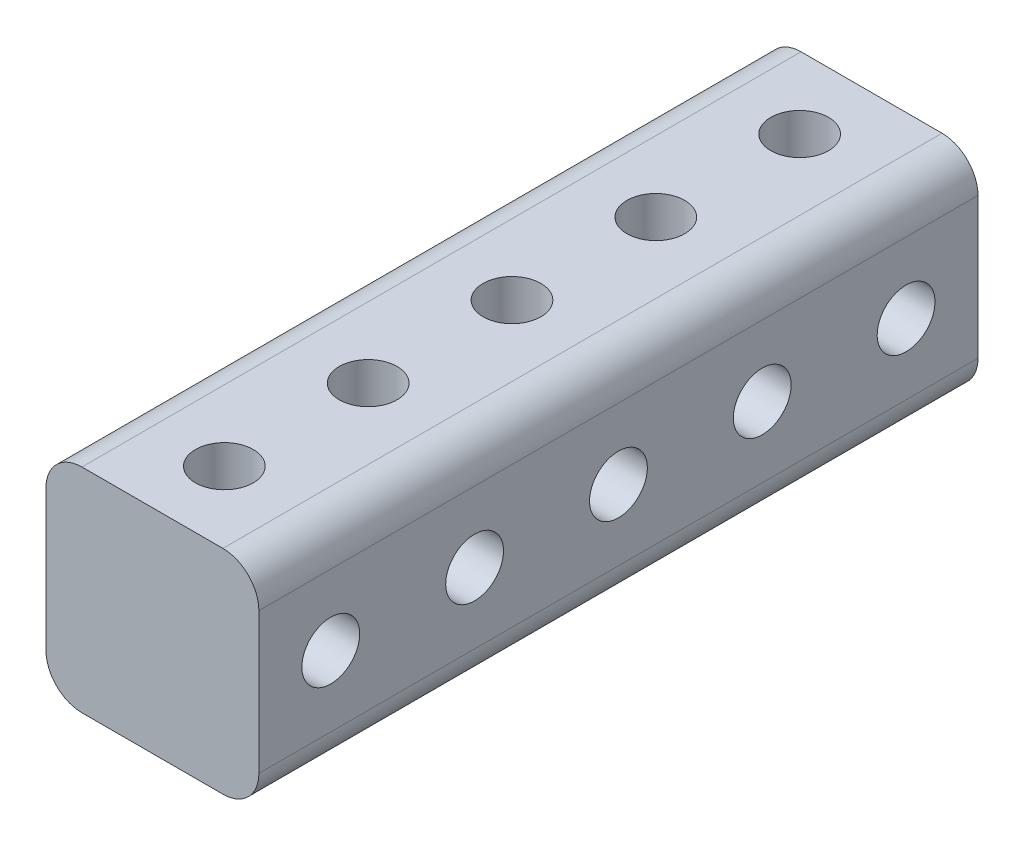
SolidWorks part; units mm, degrees
material "PET"
ref_plane "Front Plane" through (0, 0, 0) normal (0, 0, 1) x (1, 0, 0)
ref_plane "Top Plane" through (0, 0, 0) normal (0, 1, 0) x (1, 0, 0)
ref_plane "Right Plane" through (0, 0, 0) normal (1, 0, 0) x (0, 0, -1)
sketch "Sketch1" plane through (0, 0, 0) normal (0, 0, 1) x (1, 0, 0)
  line L1 (0, 0) -> (18.796, 0)
  line L2 (0, 0) -> (0, 18.796)
  line L3 (0, 18.796) -> (18.796, 18.796)
  line L4 (18.796, 0) -> (18.796, 18.796)
  dimension "D1" = 18.796
extrude "Boss-Extrude1" add sketch "Sketch1" along normal blind 63.5
fillet "Fillet1" radius 3.175 4 edges at (0, 18.796, 31.75) (18.796, 0, 31.75) (0, 0, 31.75) (18.796, 18.796, 31.75)
sketch "Sketch2" plane through (0, 18.796, 0) normal (0, 1, 0) x (1, 0, 0)
  line L0 (15.621, 0) -> (3.175, 0) construction
  line L2 (9.398, 0) -> (9.398, -63.5) construction
  line L3 (15.621, -63.5) -> (3.175, -63.5) construction
  circle A0 centre (9.398, -6.35) radius 2.5527
  circle A1 centre (9.398, -19.05) radius 2.5527
  circle A2 centre (9.398, -31.75) radius 2.5527
  circle A3 centre (9.398, -44.45) radius 2.5527
  circle A4 centre (9.398, -57.15) radius 2.5527
  dimension "D1" = 5.1054
  dimension "D4" = 12.7
  dimension "D2" = 6.35
  dimension "D3" = 5
extrude "Cut-Extrude1" cut sketch "Sketch2" against normal blind 63.5
sketch "Sketch3" plane through (18.796, 0, 0) normal (1, 0, 0) x (0, 0, -1)
  line L0 (-63.5, 3.175) -> (-63.5, 15.621) construction
  line L1 (-63.5, 9.398) -> (0, 9.398) construction
  line L2 (0, 3.175) -> (0, 15.621) construction
  circle A0 centre (-57.15, 9.398) radius 2.5527
  circle A1 centre (-44.45, 9.398) radius 2.5527
  circle A2 centre (-31.75, 9.398) radius 2.5527
  circle A3 centre (-19.05, 9.398) radius 2.5527
  circle A4 centre (-6.35, 9.398) radius 2.5527
  dimension "D2" = 5.1054
  dimension "D4" = 12.7
  dimension "D1" = 6.35
  dimension "D3" = 5
extrude "Cut-Extrude2" cut sketch "Sketch3" against normal blind 63.5
